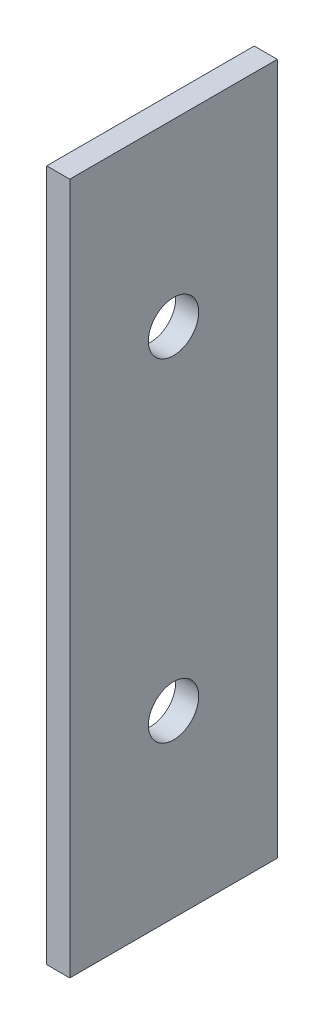
SolidWorks part; units mm, degrees
ref_plane "Front Plane" through (0, 0, 0) normal (0, 0, 1) x (1, 0, 0)
ref_plane "Top Plane" through (0, 0, 0) normal (0, 1, 0) x (1, 0, 0)
ref_plane "Right Plane" through (0, 0, 0) normal (1, 0, 0) x (0, 0, -1)
sketch "Sketch1" plane through (0, 0, 0) normal (0, 0, 1) x (1, 0, 0)
  line L1 (2.1292, 7.0575) -> (3.1292, 7.0575)
  line L2 (2.1292, 7.0575) -> (2.1292, -22.9425)
  line L3 (2.1292, -22.9425) -> (3.1292, -22.9425)
  line L4 (3.1292, 7.0575) -> (3.1292, -22.9425)
  line L10 (3.1292, -4.9425) -> (3.1292, -22.9425)
  dimension "D1" = 30
  dimension "D3" = 1
extrude "Boss-Extrude1" add sketch "Sketch1" along normal blind 9
sketch "Sketch2" plane through (3.1292, 0, 0) normal (1, 0, 0) x (0, 0, -1)
  line L0 (-4.5, 7.0575) -> (-4.5, -22.9425) construction
  line L1 (-9, 7.0575) -> (0, 7.0575) construction
  line L2 (-9, -22.9425) -> (0, -22.9425) construction
  line L3 (-9, 7.0575) -> (-9, -22.9425) construction
  line L4 (0, -7.9425) -> (-9, -7.9425) construction
  line L5 (0, 7.0575) -> (0, -22.9425) construction
  circle A0 centre (-4.5, -0.7275) radius 1.0922
  circle A1 centre (-4.5, -15.1575) radius 1.0922
  dimension "D1" = 2.1844
  dimension "D2" = 14.43
  dimension "D3" = 7.785
extrude "Cut-Extrude1" cut sketch "Sketch2" against normal blind 10
